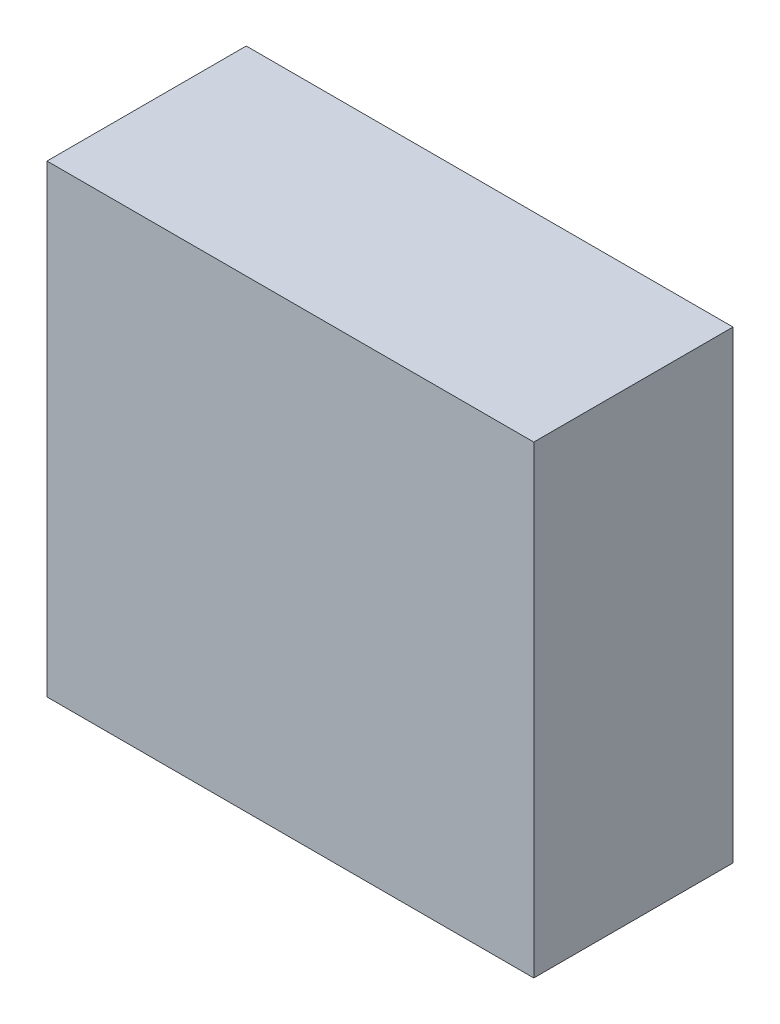
SolidWorks part; units mm, degrees
ref_plane "Front Plane" through (0, 0, 0) normal (0, 0, 1) x (1, 0, 0)
ref_plane "Top Plane" through (0, 0, 0) normal (0, 1, 0) x (1, 0, 0)
ref_plane "Right Plane" through (0, 0, 0) normal (1, 0, 0) x (0, 0, -1)
sketch "Sketch1" plane through (0, 0, 0) normal (0, 0, 1) x (1, 0, 0)
  line L1 (-21.5, -20.5) -> (21.5, -20.5)
  line L2 (-21.5, -20.5) -> (-21.5, 20.5)
  line L3 (-21.5, 20.5) -> (21.5, 20.5)
  line L4 (21.5, -20.5) -> (21.5, 20.5)
  line L5 (-21.5, -20.5) -> (21.5, 20.5) construction
  line L6 (-21.5, 20.5) -> (21.5, -20.5) construction
  point P0 (0, 0)
extrude "Envelope" add sketch "Sketch1" along normal blind 17.6
